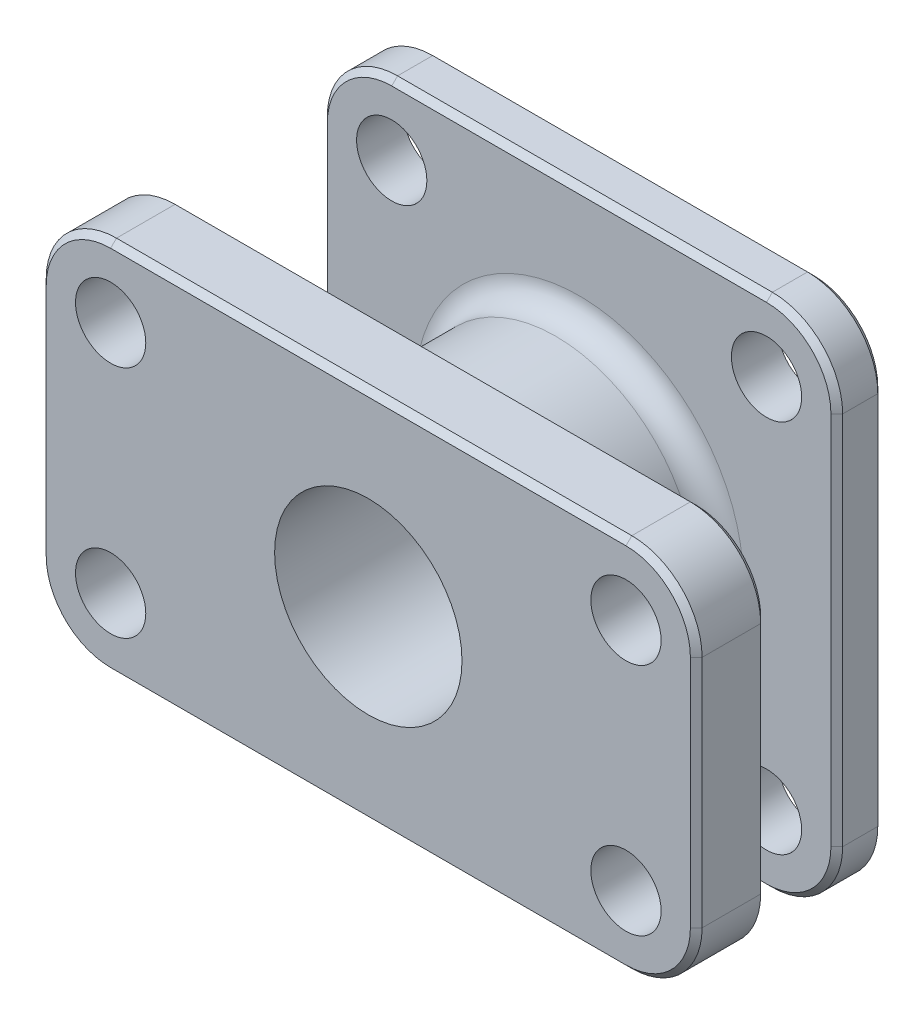
SolidWorks part; units mm, degrees
ref_plane "Front Plane" through (0, 0, 0) normal (0, 0, 1) x (1, 0, 0)
ref_plane "Top Plane" through (0, 0, 0) normal (0, 1, 0) x (1, 0, 0)
ref_plane "Right Plane" through (0, 0, 0) normal (1, 0, 0) x (0, 0, -1)
sketch "Sketch1" plane through (0, 0, 0) normal (0, 0, 1) x (1, 0, 0)
  line L1 (8, -11) -> (-8, -11)
  line L2 (11, -8) -> (11, 8)
  line L3 (8, 11) -> (-8, 11)
  line L4 (-11, -8) -> (-11, 8)
  line L5 (11, -11) -> (-11, 11) construction
  line L6 (11, 11) -> (-11, -11) construction
  arc A0 (11, 8) -> (8, 11) centre (8, 8) ccw
  arc A1 (8, -11) -> (11, -8) centre (8, -8) ccw
  arc A2 (-8, -11) -> (-11, -8) centre (-8, -8) cw
  arc A3 (-8, 11) -> (-11, 8) centre (-8, 8) ccw
  circle A4 centre (-8, 8) radius 1.5
  circle A5 centre (8, 8) radius 1.5
  circle A6 centre (8, -8) radius 1.5
  circle A7 centre (-8, -8) radius 1.5
  point P0 (0, 0)
  dimension "D3" = 3
  dimension "D4" = 3
  dimension "D1" = 11
  dimension "D2" = 11
extrude "Boss-Extrude1" add sketch "Sketch1" along normal blind 2
sketch "Sketch2" plane through (0, 0, 2) normal (0, 0, 1) x (1, 0, 0)
  circle A0 centre (0, 0) radius 6
  dimension "D1" = 12
extrude "Boss-Extrude2" add sketch "Sketch2" along normal blind 6
sketch "Sketch3" plane through (0, 0, 8) normal (0, 0, 1) x (1, 0, 0)
  line L1 (11, -8) -> (-11, -8)
  line L2 (14, -5) -> (14, 5)
  line L3 (11, 8) -> (-11, 8)
  line L4 (-14, -5) -> (-14, 5)
  line L5 (14, -8) -> (-14, 8) construction
  line L6 (14, 8) -> (-14, -8) construction
  arc A1 (-11, -8) -> (-14, -5) centre (-11, -5) cw
  arc A2 (11, -8) -> (14, -5) centre (11, -5) ccw
  arc A3 (14, 5) -> (11, 8) centre (11, 5) ccw
  arc A4 (-11, 8) -> (-14, 5) centre (-11, 5) ccw
  circle A5 centre (-11, 5) radius 1.5
  circle A6 centre (11, 5) radius 1.5
  circle A7 centre (11, -5) radius 1.5
  circle A8 centre (-11, -5) radius 1.5
  point P0 (0, 0)
  dimension "D3" = 3
  dimension "D4" = 3
  dimension "D1" = 8
  dimension "D2" = 14
extrude "Boss-Extrude3" add sketch "Sketch3" along normal blind 3
sketch "Sketch4" plane through (0, 0, 0) normal (0, 0, -1) x (-1, 0, 0)
  circle A0 centre (0, 0) radius 4
  dimension "D1" = 8
extrude "Cut-Extrude1" cut sketch "Sketch4" against normal through all
chamfer "Chamfer1" distance 2 angle 45 1 edges at (-4, 0, 0)
fillet "Fillet1" radius 1 2 edges at (6, 0, 2) (6, 0, 8)
chamfer "Chamfer2" distance 0.25 angle 45 32 edges at (0, -8, 11) (13.1213, -7.1213, 11) (-13.1213, -7.1213, 11) (14, 0, 11) (-14, 0, 11) (13.1213, 7.1213, 11) (-13.1213, 7.1213, 11) (0, 8, 11) (0, -8, 8) (13.1213, -7.1213, 8) (-13.1213, -7.1213, 8) (14, 0, 8) (-14, 0, 8) (13.1213, 7.1213, 8) (-13.1213, 7.1213, 8) (0, 8, 8) (0, -11, 2) (10.1213, -10.1213, 2) (-10.1213, -10.1213, 2) (11, 0, 2) (-11, 0, 2) (10.1213, 10.1213, 2) (-10.1213, 10.1213, 2) (0, 11, 2) (0, -11, 0) (10.1213, -10.1213, 0) (-10.1213, -10.1213, 0) (11, 0, 0) (-11, 0, 0) (10.1213, 10.1213, 0) (-10.1213, 10.1213, 0) (0, 11, 0)
